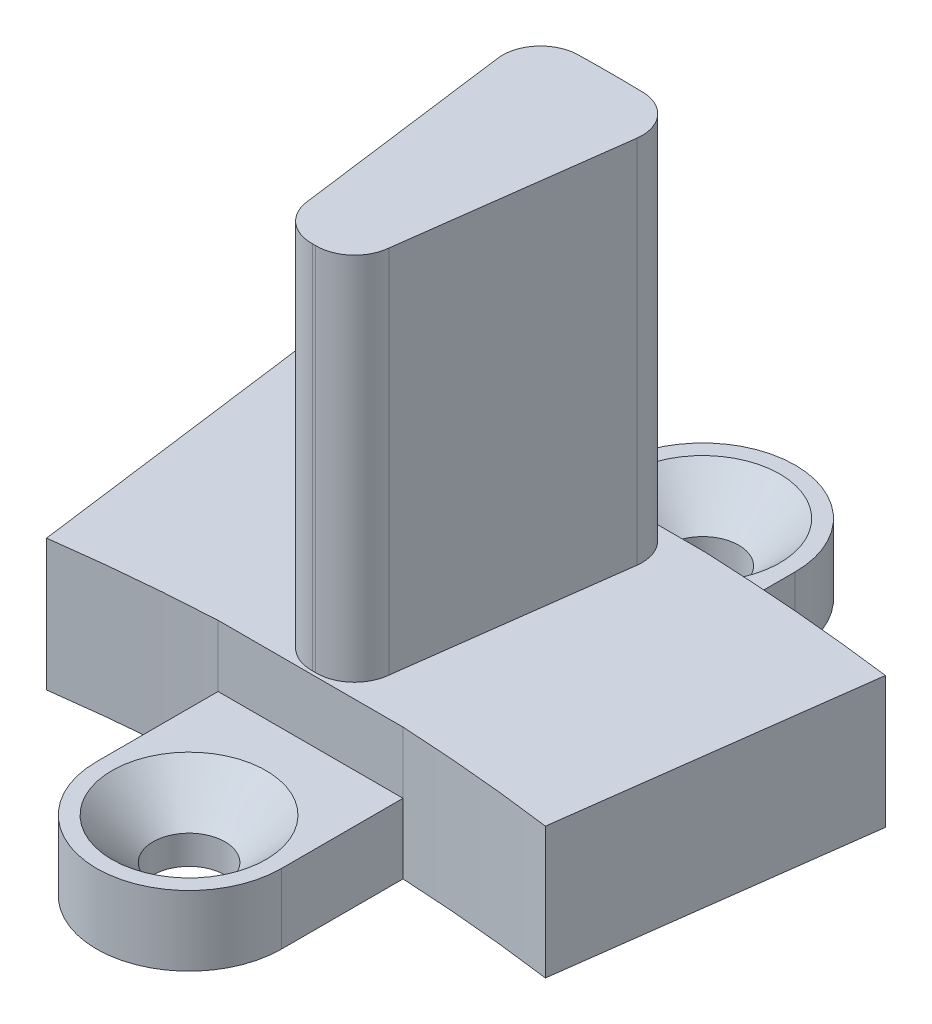
SolidWorks part; units mm, degrees
ref_plane "Front Plane" through (0, 0, 0) normal (0, 0, 1) x (1, 0, 0)
ref_plane "Top Plane" through (0, 0, 0) normal (0, 1, 0) x (1, 0, 0)
ref_plane "Right Plane" through (0, 0, 0) normal (1, 0, 0) x (0, 0, -1)
sketch "Sketch1" plane through (0, 0, 0) normal (0, 1, 0) x (1, 0, 0)
  line L0 (-42.0952, 101.6267) -> (-34.716, 83.8117) construction
  line L1 (34.716, 83.8117) -> (42.0952, 101.6267) construction
  line L2 (0, 90.7172) -> (0, 171.0298) construction
  line L3 (-34.716, 83.8117) -> (0, 0) construction
  line L4 (0, 0) -> (0, 90.7172) construction
  line L5 (0, 0) -> (34.716, 83.8117) construction
  line L6 (14.0642, 106.8282) -> (12.1389, 92.2044) construction
  line L7 (-14.0642, 106.8282) -> (-12.1389, 92.2044) construction
  line L8 (-14.0642, 106.8282) -> (-12.1389, 92.2044)
  line L9 (12.1389, 92.2044) -> (14.0642, 106.8282)
  line L10 (13.0994, 99.5) -> (-13.0994, 99.5) construction
  line L11 (-4.5, 112) -> (-4.5, 109.9079)
  line L12 (4.5, 112) -> (4.5, 109.9079)
  line L13 (4.5, 87) -> (4.5, 89.0921)
  line L14 (-4.5, 87) -> (-4.5, 89.0921)
  line L15 (-4.5, 89.0921) -> (-4.5, 90.6055)
  line L16 (4.5, 89.0921) -> (4.5, 90.6055)
  line L17 (-4.5, 90.6055) -> (-4.5, 92.9142)
  line L18 (4.5, 90.6055) -> (4.5, 92.9142)
  line L19 (-4.5, 109.9079) -> (-4.5, 107.6389)
  line L20 (4.5, 109.9079) -> (4.5, 107.6389)
  line L21 (12.1389, 92.2044) -> (11.841, 89.9411) construction
  line L22 (11.841, 89.9411) -> (0, 0) construction
  line L23 (11.841, 89.9411) -> (12.1389, 92.2044) construction
  line L24 (-12.1389, 92.2044) -> (-11.841, 89.9411) construction
  line L25 (-11.841, 89.9411) -> (0, 0) construction
  line L26 (-12.1389, 92.2044) -> (-11.841, 89.9411) construction
  line L27 (14.3579, 109.0589) -> (14.0642, 106.8282) construction
  line L28 (14.0642, 106.8282) -> (14.3579, 109.0589) construction
  line L29 (-14.3579, 109.0589) -> (-14.0642, 106.8282) construction
  line L30 (-14.3579, 109.0589) -> (-14.0642, 106.8282) construction
  arc A0 (-14.3579, 109.0589) -> (14.3579, 109.0589) centre (0, 0) ccw construction
  arc A1 (42.0952, 101.6267) -> (14.3579, 109.0589) centre (0, 0) ccw construction
  arc A3 (14.3579, 109.0589) -> (4.5, 109.9079) centre (0, 0) ccw construction
  circle A5 centre (0, 112) radius 1.75
  circle A6 centre (0, 87) radius 1.75
  arc A7 (-4.5, 112) -> (4.5, 112) centre (0, 112) cw
  arc A8 (0, 110) -> (-4.5, 109.9079) centre (0, 0) ccw construction
  arc A9 (-4.5, 109.9079) -> (-14.3579, 109.0589) centre (0, 0) ccw construction
  arc A10 (0, 110) -> (-4.5, 109.9079) centre (0, 0) ccw construction
  arc A11 (0, 110) -> (-4.5, 109.9079) centre (0, 0) ccw construction
  arc A12 (-14.3579, 109.0589) -> (-42.0952, 101.6267) centre (0, 0) ccw construction
  arc A13 (4.5, 109.9079) -> (0, 110) centre (0, 0) ccw construction
  arc A14 (4.5, 109.9079) -> (0, 110) centre (0, 0) ccw construction
  arc A15 (4.5, 109.9079) -> (0, 110) centre (0, 0) ccw construction
  arc A16 (-4.5, 87) -> (4.5, 87) centre (0, 87) ccw
  arc A18 (14.3579, 109.0589) -> (4.5, 109.9079) centre (0, 0) ccw construction
  arc A23 (-4.5, 92.9142) -> (-12.1389, 92.2044) centre (0, 3.0268) ccw
  arc A24 (12.1389, 92.2044) -> (4.5, 92.9142) centre (0, 3.0268) ccw
  arc A25 (14.0642, 106.8282) -> (4.5, 107.6389) centre (0, -2.269) ccw
  arc A26 (-4.5, 107.6389) -> (-14.0642, 106.8282) centre (0, -2.269) ccw
  arc A27 (14.3579, 109.0589) -> (4.5, 109.9079) centre (0, 0) ccw construction
  arc A28 (-4.5, 109.9079) -> (-14.3579, 109.0589) centre (0, 0) ccw construction
  arc A29 (-4.5, 109.9079) -> (-14.3579, 109.0589) centre (0, 0) ccw construction
  dimension "D1" = 220
  dimension "D2" = 45
  dimension "D3" = 90
  dimension "D4" = 15
  dimension "D5" = 3.5
  dimension "D7" = 9
  dimension "D11" = 110
  dimension "D6" = 12.5
  dimension "D8" = 112
  dimension "D9" = 17
  dimension "D10" = 2.25
extrude "Boss-Extrude1" add sketch "Sketch1" along normal mid plane 6.4
sketch "Sketch3" plane through (0, 3.2, 0) normal (0, 1, 0) x (1, 0, 0)
  line L0 (0, 100) -> (0, 141.737) construction
  line L1 (2.3796, 94.7356) -> (3.7828, 105.3936) construction
  line L2 (-15.3858, 117.2881) -> (-10.85, 82.8354) construction
  line L3 (-10.85, 82.8354) -> (10.85, 82.8354) construction
  line L4 (10.85, 82.8354) -> (15.3858, 117.2881) construction
  line L5 (-3.7828, 105.3936) -> (-2.3796, 94.7356) construction
  line L6 (-0.14, 94.9515) -> (0.14, 94.9515) construction
  line L7 (-1.55, 105.6715) -> (1.55, 105.6715) construction
  line L8 (0, 0) -> (0, 185.4872) construction
  line L9 (0, 0) -> (-64.4427, 155.5785) construction
  line L10 (17.4522, 116.9822) -> (12.825, 82.5416) construction
  line L11 (12.825, 82.5416) -> (33.7706, 76.8696) construction
  line L12 (33.7706, 76.8696) -> (47.154, 108.939) construction
  line L15 (2.1809, 94.7581) -> (3.5844, 105.419) construction
  line L16 (-3.5844, 105.419) -> (-2.1809, 94.7581) construction
  line L17 (-33.7706, 76.8696) -> (-47.154, 108.939) construction
  line L18 (-12.825, 82.5416) -> (-33.7706, 76.8696) construction
  line L19 (-17.4522, 116.9822) -> (-12.825, 82.5416) construction
  line L22 (-0.1168, -6.3136) -> (-38.8981, 138.4201) construction
  line L23 (28.7052, 90.5701) -> (32.8454, 100.4909) [skipped]
  line L24 (25.5428, 102.4684) -> (24.1114, 91.8141) [skipped]
  line L25 (28.6681, 91.6847) -> (32.7545, 101.6277) construction
  line L26 (25.4414, 103.5656) -> (24.0677, 92.9038) construction
  line L27 (1.9666, 94.7607) -> (3.3705, 105.4245)
  line L28 (-3.386, 105.4307) -> (-1.9821, 94.7669)
  line L29 (-25.4414, 103.5656) -> (-24.0677, 92.9038) construction
  line L30 (-28.6681, 91.6847) -> (-32.7545, 101.6277) construction
  line L31 (1.3856, 94.8463) -> (2.7908, 105.5201) construction
  line L32 (-2.7908, 105.5201) -> (-1.3856, 94.8463) construction
  line L33 (27.7356, 92.0464) -> (31.828, 102.0041) construction
  line L34 (26.4327, 103.4338) -> (25.0569, 92.7562) construction
  line L35 (-27.7356, 92.0464) -> (-31.828, 102.0041) construction
  line L36 (-26.4327, 103.4338) -> (-25.0569, 92.7562) construction
  arc A0 (3.5844, 105.419) -> (1.6433, 107.7194) centre (1.55, 105.6715) ccw construction
  arc A1 (15.3858, 117.2881) -> (-15.3858, 117.2881) centre (0, 34.7091) ccw construction
  arc A2 (-2.3796, 94.7356) -> (-0.8932, 92.8314) centre (-0.14, 94.9515) ccw construction
  arc A3 (-0.619, 92.8334) -> (2.3796, 94.7356) centre (0.14, 94.9515) ccw construction
  arc A4 (-0.619, 92.8334) -> (-0.8932, 92.8314) centre (0, -7.1646) ccw construction
  arc A5 (3.7828, 105.3936) -> (1.65, 107.9193) centre (1.55, 105.6715) ccw construction
  arc A6 (1.65, 107.9193) -> (-1.65, 107.9193) centre (0, 35.0203) ccw construction
  arc A7 (-1.65, 107.9193) -> (-3.7828, 105.3936) centre (-1.55, 105.6715) ccw construction
  arc A8 (47.154, 108.939) -> (17.4522, 116.9822) centre (10.7185, 33.2525) ccw construction
  arc A15 (-47.154, 108.939) -> (-17.4522, 116.9822) centre (-10.7185, 33.2525) cw construction
  arc A22 (32.8454, 100.4909) -> (31.4469, 103.4863) centre (30.7629, 101.3428) ccw [skipped]
  arc A23 (31.4469, 103.4863) -> (28.2616, 104.3488) centre (10.7999, 33.5528) ccw [skipped]
  arc A24 (28.2616, 104.3488) -> (25.5428, 102.4684) centre (27.7706, 102.1531) ccw [skipped]
  arc A25 (24.1114, 91.8141) -> (25.0484, 89.5876) centre (26.3296, 91.4372) ccw [skipped]
  arc A26 (25.3136, 89.5179) -> (25.0484, 89.5876) centre (-0.2265, -7.1656) ccw [skipped]
  arc A27 (25.3136, 89.5179) -> (28.7052, 90.5701) centre (26.5999, 91.364) ccw [skipped]
  arc A28 (32.7545, 101.6277) -> (31.3399, 104.6155) centre (30.6674, 102.4683) ccw construction
  arc A29 (31.3399, 104.6155) -> (28.1499, 105.4608) centre (11.0719, 34.5712) ccw construction
  arc A30 (28.1499, 105.4608) -> (25.4414, 103.5656) centre (27.6708, 103.2624) ccw construction
  arc A31 (24.0677, 92.9038) -> (25.0167, 90.6823) centre (26.2879, 92.5388) ccw construction
  arc A32 (25.2823, 90.6141) -> (25.0167, 90.6823) centre (0.2662, -6.2063) ccw construction
  arc A33 (25.2823, 90.6141) -> (28.6681, 91.6847) centre (26.5585, 92.4671) ccw construction
  arc A34 (-25.2823, 90.6141) -> (-28.6681, 91.6847) centre (-26.5585, 92.4671) cw construction
  arc A35 (-25.2823, 90.6141) -> (-25.0167, 90.6823) centre (-0.2662, -6.2063) cw construction
  arc A36 (-24.0677, 92.9038) -> (-25.0167, 90.6823) centre (-26.2879, 92.5388) cw construction
  arc A37 (-28.1499, 105.4608) -> (-25.4414, 103.5656) centre (-27.6708, 103.2624) cw construction
  arc A38 (-31.3399, 104.6155) -> (-28.1499, 105.4608) centre (-11.0719, 34.5712) cw construction
  arc A39 (-32.7545, 101.6277) -> (-31.3399, 104.6155) centre (-30.6674, 102.4683) cw construction
  arc A40 (2.7908, 105.5201) -> (1.6149, 106.9199) centre (1.55, 105.6715) ccw construction
  arc A41 (1.6149, 106.9199) -> (-1.6149, 106.9199) centre (0, 35.0203) ccw construction
  arc A42 (-1.6149, 106.9199) -> (-2.7908, 105.5201) centre (-1.55, 105.6715) ccw construction
  arc A43 (-1.3856, 94.8463) -> (-0.6979, 93.8329) centre (-0.14, 94.9515) ccw construction
  arc A44 (-0.4209, 93.8345) -> (-0.6979, 93.8329) centre (0, -7.1646) ccw construction
  arc A45 (-0.4209, 93.8345) -> (1.3856, 94.8463) centre (0.14, 94.9515) ccw construction
  arc A46 (31.828, 102.0041) -> (31.0499, 103.6583) centre (30.6674, 102.4683) ccw construction
  arc A47 (31.0499, 103.6583) -> (27.9278, 104.4857) centre (11.0719, 34.5712) ccw construction
  arc A48 (27.9278, 104.4857) -> (26.4327, 103.4338) centre (27.6708, 103.2624) ccw construction
  arc A49 (25.0569, 92.7562) -> (25.4621, 91.6005) centre (26.2879, 92.5388) ccw construction
  arc A50 (25.7302, 91.531) -> (25.4621, 91.6005) centre (0.2662, -6.2063) ccw construction
  arc A51 (25.7302, 91.531) -> (27.7356, 92.0464) centre (26.5585, 92.4671) ccw construction
  arc A52 (-25.7302, 91.531) -> (-27.7356, 92.0464) centre (-26.5585, 92.4671) cw construction
  arc A53 (-31.828, 102.0041) -> (-31.0499, 103.6583) centre (-30.6674, 102.4683) cw construction
  arc A54 (-31.0499, 103.6583) -> (-27.9278, 104.4857) centre (-11.0719, 34.5712) cw construction
  arc A55 (-27.9278, 104.4857) -> (-26.4327, 103.4338) centre (-27.6708, 103.2624) cw construction
  arc A56 (-25.0569, 92.7562) -> (-25.4621, 91.6005) centre (-26.2879, 92.5388) cw construction
  arc A57 (-25.7302, 91.531) -> (-25.4621, 91.6005) centre (-0.2662, -6.2063) cw construction
  arc A58 (1.6433, 107.7194) -> (-1.6433, 107.7194) centre (0, 35.0203) ccw construction
  arc A59 (-1.6433, 107.7194) -> (-3.5844, 105.419) centre (-1.55, 105.6715) ccw construction
  arc A60 (-2.1809, 94.7581) -> (-0.8587, 93.0317) centre (-0.14, 94.9515) ccw construction
  arc A61 (-0.584, 93.0336) -> (-0.8587, 93.0317) centre (0, -7.1646) ccw construction
  arc A62 (-0.584, 93.0336) -> (2.1809, 94.7581) centre (0.14, 94.9515) ccw construction
  arc A63 (3.3705, 105.4245) -> (1.6364, 107.5059) centre (1.5354, 105.6587) ccw
  arc A64 (1.6364, 107.5059) -> (-1.6364, 107.5059) centre (0, 34.9826) ccw
  arc A65 (-1.6364, 107.5059) -> (-3.386, 105.4307) centre (-1.55, 105.6579) ccw
  arc A66 (-1.9821, 94.7669) -> (-0.0685, 93.0809) centre (-0.1195, 94.952) ccw
  arc A67 (0.0685, 93.0809) -> (-0.0685, 93.0809) centre (0, -7.1646) ccw
  arc A68 (0.0685, 93.0809) -> (1.9666, 94.7607) centre (0.1244, 94.9301) ccw
  point P25 (0, 105.6715)
  point P26 (0, 94.9515)
  point P27 (0, 82.8354)
  point P157 (0.1643, 93.0865)
  point P160 (0, 0)
  point P161 (-0.0685, 93.0872)
  dimension "D3" = 100
  dimension "D4" = 2.25
  dimension "D5" = 10.72
  dimension "D6" = 15
  dimension "D7" = 2.25
  dimension "D11" = 84
  dimension "D15" = 22.5
  dimension "D21" = 1
  dimension "D20" = 100.2456
  dimension "D1" = 3.1
  dimension "D2" = 0.28
  dimension "D8" = 10.75
  dimension "D9" = 15
  dimension "D10" = 34.75
  dimension "D12" = 21.7
  dimension "D13" = 15
  dimension "D14" = 90
  dimension "D17" = 0.8
  dimension "D18" = 15
  dimension "D16" = 2
  dimension "D19" = 2
extrude "Boss-Extrude2" add sketch "Sketch3" along normal blind 18 and the other way up to surface (6.4 mm away) other way up to face at (0, -3.2, -99.7952)
sketch "Sketch4" plane through (0, 3.2, 0) normal (0, 1, 0) x (1, 0, 0)
  line L3 (13.1016, 99.5163) -> (-13.1016, 99.5163) construction
  line L4 (12.1389, 92.2044) -> (14.0642, 106.8282) construction
  line L5 (-14.0642, 106.8282) -> (-12.1389, 92.2044) construction
  line L12 (-4.5, 91.3937) -> (-4.5, 87.0326)
  line L13 (4.5, 107.6389) -> (-4.5, 107.6389)
  line L14 (-4.5, 107.6389) -> (-4.5, 112)
  line L15 (4.5, 112) -> (4.5, 107.6389)
  line L16 (4.5, 91.3937) -> (-4.5, 91.3937) construction
  line L17 (4.5, 87.0326) -> (4.5, 91.3937)
  line L18 (-4.5, 91.3937) -> (-4.5, 92.9142)
  line L19 (-4.5, 92.9142) -> (4.5, 92.9142)
  line L20 (4.5, 92.9142) -> (4.5, 91.3937)
  circle A1 centre (0, 112) radius 1.75 construction
  circle A2 centre (0, 112) radius 1.75
  arc A6 (-4.5, 112) -> (4.5, 112) centre (0, 112) cw
  circle A8 centre (0, 87) radius 1.75 construction
  circle A9 centre (0, 87) radius 1.75
  arc A11 (-4.5, 87.0326) -> (4.5, 87.0326) centre (0, 86.9178) ccw
extrude "Cut-Extrude1" cut sketch "Sketch4" against normal blind 3 and the other way through all
chamfer "Chamfer1" distance 2 angle 45 2 edges at (0, 0.2, -85.25) (0, 0.2, -110.25)
